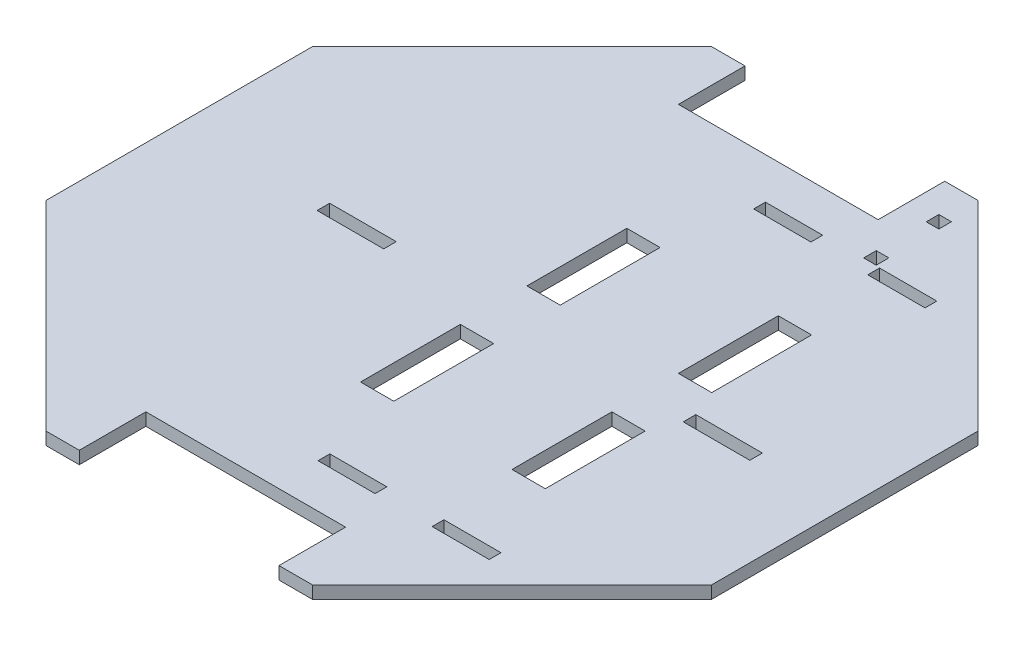
SolidWorks part; units mm, degrees
ref_plane "Front Plane" through (0, 0, 0) normal (0, 0, 1) x (1, 0, 0)
ref_plane "Top Plane" through (0, 0, 0) normal (0, 1, 0) x (1, 0, 0)
ref_plane "Right Plane" through (0, 0, 0) normal (1, 0, 0) x (0, 0, -1)
sketch "Sketch1" plane through (0, 0, 0) normal (0, 1, 0) x (1, 0, 0)
  line L1 (0, 0) -> (254, 0)
  line L2 (0, 0) -> (0, 254)
  line L3 (0, 254) -> (254, 254)
  line L4 (254, 0) -> (254, 254)
  dimension "D1" = 254
  dimension "D2" = 254
extrude "Boss-Extrude1" add sketch "Sketch1" along normal blind 4.8
sketch "Sketch2" plane through (0, 4.8, 0) normal (0, 1, 0) x (1, 0, 0)
  line L0 (0, 254) -> (76.2, 254) construction
  line L1 (254, 254) -> (0, 254) construction
  line L2 (0, 254) -> (0, 177.8) construction
  line L3 (0, 254) -> (0, 0) construction
sketch "Sketch4" plane through (0, 4.8, 0) normal (0, 1, 0) x (1, 0, 0)
  line L0 (76.2, 254) -> (0, 177.8)
  line L1 (0, 177.8) -> (0, 254)
  line L2 (0, 254) -> (76.2, 254)
extrude "Cut-Extrude2" cut sketch "Sketch4" against normal through all
sketch "Sketch5" plane through (0, 4.8, 0) normal (0, 1, 0) x (1, 0, 0)
  line L0 (177.8, 254) -> (254, 254) construction
  line L1 (254, 254) -> (76.2, 254) construction
  line L2 (254, 254) -> (254, 177.8) construction
  line L3 (254, 0) -> (254, 254) construction
  line L4 (177.8, 254) -> (254, 177.8)
  line L5 (254, 177.8) -> (254, 254)
  line L6 (254, 254) -> (177.8, 254)
extrude "Cut-Extrude3" cut sketch "Sketch5" against normal blind 4.826
sketch "Sketch9" plane through (0, 4.8, 0) normal (0, 1, 0) x (1, 0, 0)
  line L0 (0, 76.2) -> (0, 0)
  line L1 (0, 177.8) -> (0, 0) construction
  line L2 (0, 0) -> (76.2, 0)
  line L3 (0, 0) -> (254, 0) construction
  line L4 (76.2, 0) -> (0, 76.2)
  dimension "D1" = 76.2
  dimension "D2" = 76.2
extrude "Cut-Extrude5" cut sketch "Sketch9" against normal blind 4.826
sketch "Sketch11" plane through (0, 4.8, 0) normal (0, 1, 0) x (1, 0, 0)
  line L0 (254, 76.2) -> (254, 0)
  line L1 (254, 0) -> (254, 177.8) construction
  line L2 (254, 0) -> (177.8, 0)
  line L3 (76.2, 0) -> (254, 0) construction
  line L4 (177.8, 0) -> (254, 76.2)
  dimension "D1" = 76.2
  dimension "D2" = 76.2
extrude "Cut-Extrude6" cut sketch "Sketch11" against normal blind 4.826
sketch "Sketch12" plane through (0, 4.8, 0) normal (0, 1, 0) x (1, 0, 0)
  line L0 (254, 76.2) -> (254, 177.8) construction
  line L1 (194.7333, 129.4) -> (220.1333, 129.4)
  line L2 (194.7333, 129.4) -> (194.7333, 124.6)
  line L3 (194.7333, 124.6) -> (220.1333, 124.6)
  line L4 (220.1333, 129.4) -> (220.1333, 124.6)
  line L5 (194.7333, 129.4) -> (220.1333, 124.6) construction
  line L6 (194.7333, 124.6) -> (220.1333, 129.4) construction
  line L7 (177.8, 254) -> (76.2, 254) construction
  point P4 (207.4333, 127)
  dimension "D1" = 25.4
  dimension "D2" = 4.8
  dimension "D3" = 33.8667
  dimension "D4" = 124.6
extrude "Cut-Extrude7" cut sketch "Sketch12" against normal through all
sketch "Sketch13" plane through (0, 4.8, 0) normal (0, 1, 0) x (1, 0, 0)
  line L1 (55.0333, 129.4) -> (80.4333, 129.4)
  line L2 (55.0333, 129.4) -> (55.0333, 124.6)
  line L3 (55.0333, 124.6) -> (80.4333, 124.6)
  line L4 (80.4333, 129.4) -> (80.4333, 124.6)
  line L5 (55.0333, 129.4) -> (80.4333, 124.6) construction
  line L6 (55.0333, 124.6) -> (80.4333, 129.4) construction
  line L7 (0, 177.8) -> (0, 76.2) construction
  line L8 (76.2, 0) -> (177.8, 0) construction
  point P4 (67.7333, 127)
  dimension "D1" = 4.8
  dimension "D4" = 124.6
  dimension "D2" = 25.4
  dimension "D3" = 55.0333
extrude "Cut-Extrude8" cut sketch "Sketch13" against normal through all
ref_plane "Plane1" through (0, 0, -127) normal (0, 0, -1) x (-1, 0, 0)
sketch "Sketch14" plane through (0, 4.8, 0) normal (0, 1, 0) x (1, 0, 0)
  line L8 (177.8, 0) -> (254, 76.2)
  line L9 (76.2, 0) -> (177.8, 0)
  line L10 (0, 76.2) -> (76.2, 0)
  line L11 (0, 177.8) -> (0, 76.2)
  line L12 (76.2, 254) -> (0, 177.8)
  line L13 (177.8, 254) -> (76.2, 254)
  line L14 (254, 177.8) -> (177.8, 254)
  line L15 (254, 76.2) -> (254, 177.8)
  line L16 (177.8, 0) -> (254, 76.2)
  line L17 (76.2, 0) -> (177.8, 0)
  line L18 (0, 76.2) -> (76.2, 0)
  line L19 (0, 177.8) -> (0, 76.2)
  line L20 (76.2, 254) -> (0, 177.8)
  line L21 (177.8, 254) -> (76.2, 254)
  line L22 (254, 177.8) -> (177.8, 254)
  line L23 (254, 76.2) -> (254, 177.8)
  dimension "D1" = 0
sketch "Sketch18" plane through (0, 4.8, 0) normal (0, 1, 0) x (1, 0, 0)
  line L3 (165.1, 25.4) -> (165.1, 0)
  line L4 (88.9, 25.4) -> (165.1, 25.4)
  line L5 (88.9, 25.4) -> (88.9, 0)
  line L7 (165.1, 0) -> (88.9, 0)
extrude "Cut-Extrude15" cut sketch "Sketch18" against normal through all
ref_plane "Plane2" through (0, 0, -127) normal (0, 0, 1) x (1, 0, 0)
mirror "Mirror1" about plane through (0, 0, -127) normal (0, 0, 1) of "Cut-Extrude15"
sketch "Sketch19" plane through (0, 0, 0) normal (0, -1, 0) x (1, 0, 0)
  line L0 (195.9429, -210.0517) -> (203.2, -210.0517)
  line L6 (203.2, -212.4517) -> (181.356, -212.4517)
  line L11 (203.2, -212.4517) -> (203.2, -207.9517)
  line L12 (203.2, -207.9517) -> (181.356, -207.9517)
  line L16 (174.1714, -212.3737) -> (174.1714, -207.5737) construction
  line L17 (174.1714, -207.5737) -> (152.4, -207.5737) construction
  line L18 (152.4, -207.5737) -> (152.4, -212.3737) construction
  line L19 (152.4, -212.3737) -> (174.1714, -212.3737) construction
  line L20 (217.7143, -207.6517) -> (195.9429, -207.6517) construction
  line L21 (195.9429, -207.6517) -> (195.9429, -212.4517) construction
  line L22 (195.9429, -212.4517) -> (217.7143, -212.4517) construction
  line L23 (217.7143, -212.4517) -> (217.7143, -207.6517) construction
  line L24 (174.1624, -46.45) -> (174.1624, -41.65) construction
  line L25 (174.1624, -41.65) -> (152.403, -41.65) construction
  line L26 (152.403, -41.65) -> (152.403, -46.45) construction
  line L27 (152.403, -46.45) -> (174.1624, -46.45) construction
  line L28 (217.6931, -41.65) -> (195.9338, -41.65) construction
  line L29 (195.9338, -41.65) -> (195.9338, -46.45) construction
  line L30 (195.9338, -46.45) -> (217.6931, -46.45) construction
  line L31 (217.6931, -46.45) -> (217.6931, -41.65) construction
  line L33 (181.356, -212.4517) -> (181.356, -207.9517)
  line L34 (203.2, -212.4517) -> (181.356, -207.9517) construction
  line L39 (203.2, -207.9517) -> (181.356, -212.4517) construction
  line L40 (217.7143, -210.0517) -> (195.9429, -210.0517) construction
  line L41 (159.766, -212.3737) -> (137.922, -212.3737)
  line L42 (159.766, -212.3737) -> (159.766, -207.8737)
  line L43 (159.766, -207.8737) -> (137.922, -207.8737)
  line L44 (137.922, -212.3737) -> (137.922, -207.8737)
  line L45 (159.766, -212.3737) -> (137.922, -207.8737) construction
  line L46 (159.766, -207.8737) -> (137.922, -212.3737) construction
  line L47 (203.2, -46.45) -> (181.356, -46.45)
  line L48 (203.2, -46.45) -> (203.2, -41.65)
  line L50 (203.2, -41.65) -> (181.356, -41.65)
  line L51 (181.356, -46.45) -> (181.356, -41.65)
  line L52 (203.2, -46.45) -> (181.356, -41.65) construction
  line L53 (203.2, -41.65) -> (181.356, -46.45) construction
  line L54 (159.766, -46.45) -> (137.922, -46.45)
  line L55 (159.766, -46.45) -> (159.766, -41.65)
  line L56 (159.766, -41.65) -> (137.922, -41.65)
  line L57 (137.922, -46.45) -> (137.922, -41.65)
  line L58 (159.766, -46.45) -> (137.922, -41.65) construction
  line L59 (159.766, -41.65) -> (137.922, -46.45) construction
  point P23 (192.278, -210.2017)
  point P30 (148.844, -210.1237)
  point P33 (192.278, -44.05)
  point P38 (148.844, -44.05)
extrude "Cut-Extrude16" [suppressed] cut sketch "Sketch19" against normal through all
sketch "Sketch20" plane through (0, 0, 0) normal (0, -1, 0) x (1, 0, 0)
  line L0 (174.1714, -213.1851) -> (174.1714, -208.3851) construction
  line L1 (174.1714, -208.3851) -> (152.4, -208.3851) construction
  line L2 (152.4, -208.3851) -> (152.4, -213.1851) construction
  line L3 (152.4, -213.1851) -> (174.1714, -213.1851) construction
  line L4 (217.7143, -208.3851) -> (195.9429, -208.3851) construction
  line L5 (195.9429, -208.3851) -> (195.9429, -213.1851) construction
  line L6 (195.9429, -213.1851) -> (217.7143, -213.1851) construction
  line L7 (217.7143, -213.1851) -> (217.7143, -208.3851) construction
  line L8 (174.1593, -46.6) -> (174.1593, -41.8) construction
  line L9 (174.1593, -41.8) -> (152.4, -41.8) construction
  line L10 (152.4, -41.8) -> (152.4, -46.6) construction
  line L11 (152.4, -46.6) -> (174.1593, -46.6) construction
  line L12 (217.678, -41.8) -> (195.9187, -41.8) construction
  line L13 (195.9187, -41.8) -> (195.9187, -46.6) construction
  line L14 (195.9187, -46.6) -> (217.678, -46.6) construction
  line L15 (217.678, -46.6) -> (217.678, -41.8) construction
  line L16 (174.1714, -213.1851) -> (174.1714, -208.3851)
  line L17 (174.1714, -208.3851) -> (152.4, -208.3851)
  line L18 (152.4, -208.3851) -> (152.4, -213.1851)
  line L19 (152.4, -213.1851) -> (174.1714, -213.1851)
  line L20 (217.7143, -208.3851) -> (195.9429, -208.3851)
  line L21 (195.9429, -208.3851) -> (195.9429, -213.1851)
  line L22 (195.9429, -213.1851) -> (217.7143, -213.1851)
  line L23 (217.7143, -213.1851) -> (217.7143, -208.3851)
  line L24 (174.1593, -46.6) -> (174.1593, -41.8)
  line L25 (174.1593, -41.8) -> (152.4, -41.8)
  line L26 (152.4, -41.8) -> (152.4, -46.6)
  line L27 (152.4, -46.6) -> (174.1593, -46.6)
  line L28 (217.678, -41.8) -> (195.9187, -41.8)
  line L29 (195.9187, -41.8) -> (195.9187, -46.6)
  line L30 (195.9187, -46.6) -> (217.678, -46.6)
  line L31 (217.678, -46.6) -> (217.678, -41.8)
  line L32 (195.9429, -210.7851) -> (203.2, -210.7851)
  line L33 (152.4, -210.7851) -> (159.6571, -210.7851)
  line L35 (203.2, -208.3851) -> (181.356, -208.3851)
  line L36 (203.2, -208.3851) -> (203.2, -212.8851)
  line L37 (203.2, -212.8851) -> (181.356, -212.8851)
  line L38 (181.356, -208.3851) -> (181.356, -212.8851)
  line L39 (203.2, -208.3851) -> (181.356, -212.8851) construction
  line L40 (203.2, -212.8851) -> (181.356, -208.3851) construction
  line L41 (159.6571, -208.3851) -> (137.8131, -208.3851)
  line L42 (159.6571, -208.3851) -> (159.6571, -212.8851)
  line L43 (159.6571, -212.8851) -> (137.8131, -212.8851)
  line L44 (137.8131, -208.3851) -> (137.8131, -212.8851)
  line L45 (159.6571, -208.3851) -> (137.8131, -212.8851) construction
  line L46 (159.6571, -212.8851) -> (137.8131, -208.3851) construction
  line L47 (203.2, -46.6) -> (181.4286, -46.6)
  line L48 (203.2, -46.6) -> (203.2, -42.1)
  line L49 (203.2, -42.1) -> (181.4286, -42.1)
  line L50 (181.4286, -46.6) -> (181.4286, -42.1)
  line L51 (203.2, -46.6) -> (181.4286, -42.1) construction
  line L52 (203.2, -42.1) -> (181.4286, -46.6) construction
  line L53 (159.6571, -46.6) -> (137.8857, -46.6)
  line L54 (159.6571, -46.6) -> (159.6571, -42.1)
  line L55 (159.6571, -42.1) -> (137.8857, -42.1)
  line L56 (137.8857, -46.6) -> (137.8857, -42.1)
  line L57 (159.6571, -46.6) -> (137.8857, -42.1) construction
  line L58 (159.6571, -42.1) -> (137.8857, -46.6) construction
  point P24 (192.278, -210.6351)
  point P29 (148.7351, -210.6351)
  point P34 (192.3143, -44.35)
  point P39 (148.7714, -44.35)
  dimension "D1" = 7.2571
  dimension "D2" = 7.2571
  dimension "D3" = 21.844
  dimension "D4" = 21.844
  dimension "D5" = 4.5
  dimension "D6" = 4.5
  dimension "D7" = 21.7714
  dimension "D8" = 21.7714
  dimension "D9" = 4.5
  dimension "D10" = 4.5
extrude "Cut-Extrude17" cut sketch "Sketch20" against normal through all contours L35 L38 L37 L21 | L36 L32 L21 L22 | L36 L20 L21 L32 | L42 L17 L18 L33 | L42 L33 L18 L19 | L41 L44 L43 L18 | L48 L47 L50 L49 | L54 L53 L56 L55
extrude "Cut-Extrude18" cut sketch "Sketch21" against normal through all
sketch "Sketch21" plane through (-734.8162, 4.8, 0) normal (0, 1, 0) x (0, 0, -1)
  line L0 (25.4, -912.6162) -> (76.2, -912.6162) construction
  line L1 (76.2, -925.3162) -> (114.3, -925.3162)
  line L2 (76.2, -925.3162) -> (76.2, -912.6162)
  line L3 (76.2, -912.6162) -> (114.3, -912.6162)
  line L4 (114.3, -925.3162) -> (114.3, -912.6162)
  line L5 (76.2, -925.3162) -> (114.3, -912.6162) construction
  line L6 (76.2, -912.6162) -> (114.3, -925.3162) construction
  line L7 (139.7, -925.3162) -> (177.8, -925.3162)
  line L8 (139.7, -925.3162) -> (139.7, -912.6162)
  line L9 (139.7, -912.6162) -> (177.8, -912.6162)
  line L10 (177.8, -925.3162) -> (177.8, -912.6162)
  line L11 (139.7, -925.3162) -> (177.8, -912.6162) construction
  line L12 (139.7, -912.6162) -> (177.8, -925.3162) construction
  line L13 (228.6, -912.6162) -> (177.8, -912.6162) construction
  line L16 (76.2, -734.8162) -> (76.2, -912.6162) construction
  line L17 (177.8, -734.8162) -> (177.8, -912.6162) construction
  point P4 (95.25, -918.9662)
  point P9 (158.75, -918.9662)
sketch "Sketch22" plane through (0, 0, 0) normal (0, -1, 0) x (1, 0, 0)
  line L17 (179.78, -237.0611) -> (174.98, -237.0611) construction
  line L18 (174.98, -237.0611) -> (174.98, -241.8871) construction
  line L19 (174.98, -241.8871) -> (179.78, -241.8871) construction
  line L20 (179.78, -241.8871) -> (179.78, -237.0611) construction
  line L21 (179.78, -213.1851) -> (174.98, -213.1851) construction
  line L22 (174.98, -213.1851) -> (174.98, -218.0111) construction
  line L23 (174.98, -218.0111) -> (179.78, -218.0111) construction
  line L24 (179.78, -218.0111) -> (179.78, -213.1851) construction
  line L25 (179.78, -237.0611) -> (174.98, -237.0611)
  line L26 (174.98, -237.0611) -> (174.98, -241.8871)
  line L27 (174.98, -241.8871) -> (179.78, -241.8871)
  line L28 (179.78, -241.8871) -> (179.78, -237.0611)
  line L29 (179.78, -213.1851) -> (174.98, -213.1851)
  line L30 (174.98, -213.1851) -> (174.98, -218.0111)
  line L31 (174.98, -218.0111) -> (179.78, -218.0111)
  line L32 (179.78, -218.0111) -> (179.78, -213.1851)
extrude "Cut-Extrude19" cut sketch "Sketch22" against normal through all
sketch "Sketch23" plane through (0, 4.8, 0) normal (0, 1, 0) x (1, 0, 0)
  line L0 (0, 177.8) -> (0, 76.2) construction
  line L1 (132.7, 177.8) -> (120, 177.8)
  line L2 (132.7, 177.8) -> (132.7, 139.7)
  line L3 (132.7, 139.7) -> (120, 139.7)
  line L4 (120, 177.8) -> (120, 139.7)
  line L5 (132.7, 177.8) -> (120, 139.7) construction
  line L6 (132.7, 139.7) -> (120, 177.8) construction
  line L7 (132.7, 114.3) -> (120, 114.3)
  line L8 (132.7, 114.3) -> (132.7, 76.2)
  line L9 (132.7, 76.2) -> (120, 76.2)
  line L10 (120, 114.3) -> (120, 76.2)
  line L11 (132.7, 114.3) -> (120, 76.2) construction
  line L12 (132.7, 76.2) -> (120, 114.3) construction
  line L15 (177.8, 254) -> (177.8, 177.8) construction
  line L16 (177.8, 254) -> (165.1, 254) construction
  line L18 (76.2, 0) -> (88.9, 0) construction
  point P4 (126.35, 158.75)
  point P9 (126.35, 95.25)
  dimension "D1" = 120
  dimension "D2" = 120
  dimension "D3" = 76.2
  dimension "D4" = 76.2
  dimension "D5" = 38.1
  dimension "D6" = 38.1
  dimension "D7" = 12.7
extrude "Cut-Extrude20" cut sketch "Sketch23" against normal through all
equation "\"MDF\"= 4.8mm"
equation "\"Foamcore\"= 4.6mm"
equation "\"GMaterial\"= \"MDF\""
equation "\"D1@Boss-Extrude1\"=\"GMaterial\""
equation "\"PCB\" = 1.6mm"
equation "\"BaseWidth\" = 10in"
equation "\"SkidLength\" = 1in"
equation "\"SkidClearance\" = 0.4in"
equation "\"D1@Sketch12\"=\"SkidLength\""
equation "\"D2@Sketch12\"=\"GMaterial\""
equation "\"D4@Sketch12\"=\"BaseWidth\"/2 -\"GMaterial\"/2"
equation "\"MotorMountLength\" = 2in"
equation "\"MotorMountWidth\" = \"GMaterial\""
equation "\"MotorMountHeight\" = 2.25in"
equation "\"D1@Sketch13\"=\"GMaterial\""
equation "\"D2@Sketch13\"=\"SkidLength\""
equation "\"D4@Sketch13\"=\"BaseWidth\"/2 - \"GMaterial\"/2"
equation "\"UnoStackWidth\" = 77.4mm"
equation "\"UnoStackLength\" = 79.8mm"
equation "\"UnoStackHeight\" = 34.2mm"
equation "\"TallHexRiserHeight\" = 22.2mm"
equation "\"PingPongBallSize\" = 40mm"
equation "\"BarrelLength\" = 9in"
equation "\"BarrelSize\" = \"PingPongBallSize\""
equation "\"PlatformLength\" = 4in"
equation "\"PlatformWidth\" = 6in"
equation "\"WheelDiameter\"=2.99213"
equation "\"ServoMountHeight\"=2.49223"
equation "\"ServoGearHeight\" = 0.95330261in"
equation "\"ServoMountLength\"= 1.53774"
equation "\"PivotHoleRadius\"= 0.616358"
equation "\"PlatformMountHeight\" = 3.19"
equation "\"TensionOffSet\"= .3mm"
equation "\"MotorMountWedge\"=0.333333"
equation "\"LaserCutterOffset\"= .3mm"
equation "\"BumperWidth\"=11"
equation "\"PitcherWheelCompression\" = 2.5mm"
equation "\"PitchingWheelWidth\" = 26.2mm"
equation "\"PitchingWheelDiameter\" = 65.5mm"
equation "\"PitchingWheelMountOffset\" = 8.4mm"
equation "\"PitchingWheelInnerDiameter\" = 45.5mm"
equation "\"PitchingWheelBoltShoulder\" = 4.5mm"
equation "\"BrassCouplingLength\" = 18mm"
equation "\"PitchingMotorHeight\" = 57.0mm"
equation "\"PitchingMotorShaftTopHeight\" = \"PitchingMotorHeight\" - 44.1mm"
equation "\"PitchingMotorBodyHeight\" = 38mm"
equation "\"PitchingMotorTopShoulderHeight\" = 40.6mm - \"PitchingMotorBodyHeight\" "
equation "\"PitchingMotorBottomShoulderHeight\" = 40.2mm - \"PitchingMotorBodyHeight\""
equation "\"PitchingMotorBottomShaftHeight\" = \"PitchingMotorHeight\" - \"PitchingMotorShaftTopHeight\" - \"PitchingMotorTopShoulderHeight\" - \"PitchingMotorBodyHeight\" - \"PitchingMotorBottomShoulderHeight\""
equation "\"PitchingMotorShaftDiameter\" = 2.2mm"
equation "\"PitchingMotorBodyDiameter\" = 27.4mm"
equation "\"PitchingMotorTopShoulderDiameter\" = 9.8mm"
equation "\"PitchingMotorBottomShoulderDiameter\" = 9.8mm"
equation "\"BrassCouplingHexSize\" = 12mm"
equation "\"BrassCouplingBoreSize\" = 3.17mm"
equation "\"PitchingMotorMountingHoleDistance\" = 16mm"
equation "\"Acrylic\" = 4.4mm"
equation "\"PitchingMotorDistance\" = \"PitchingWheelDiameter\" + \"PingPongBallSize\" - \"PitcherWheelCompression\"*2"
equation "\"PitchingMotorPlatformOffset\"=1"
equation "\"ServoPlatformOffset\"=1.64173"
equation "\"BallBearingDiameter\" = 22mm"
equation "\"BallBearingWidth\" = 9mm"
equation "\"BallBearingHexShoulder\" = 9mm - 5.9mm"
equation "\"BallBearingHexSize\" = .36in"
equation "\"PlatformMountFootLength\"=0.857143"
equation "\"WheelWidth\"= 26mm"
equation "\"ServoMountReductionBackHeight\"=2.25"
equation "\"PlatformBottomWidthThird\" =  0.857143in"
equation "\"PlatformMountBackReductionHeight\"= 2.5in"
equation "\"PlatformMountBackReductionWidth\"= 3/7in"
equation "\"PlatformMountFrontReductionWidth\" =  1.46226in"
equation "\"PlatformMountFrontReductionHeight\" = 2.5in"
equation "\"D1@Sketch20\"=\"PlatformMountFootLength\"/3"
equation "\"D2@Sketch20\"=\"PlatformMountFootLength\"/3"
equation "\"D5@Sketch20\"=\"GMaterial\"-\"LaserCutterOffset\""
equation "\"D6@Sketch20\"=\"GMaterial\"-\"LaserCutterOffset\""
equation "\"D7@Sketch20\"=\"PlatformMountFootLength\""
equation "\"D8@Sketch20\"=\"PlatformMountFootLength\""
equation "\"D9@Sketch20\"=\"GMaterial\"-\"LaserCutterOffset\""
equation "\"D10@Sketch20\"=\"GMaterial\"-\"LaserCutterOffset\""
